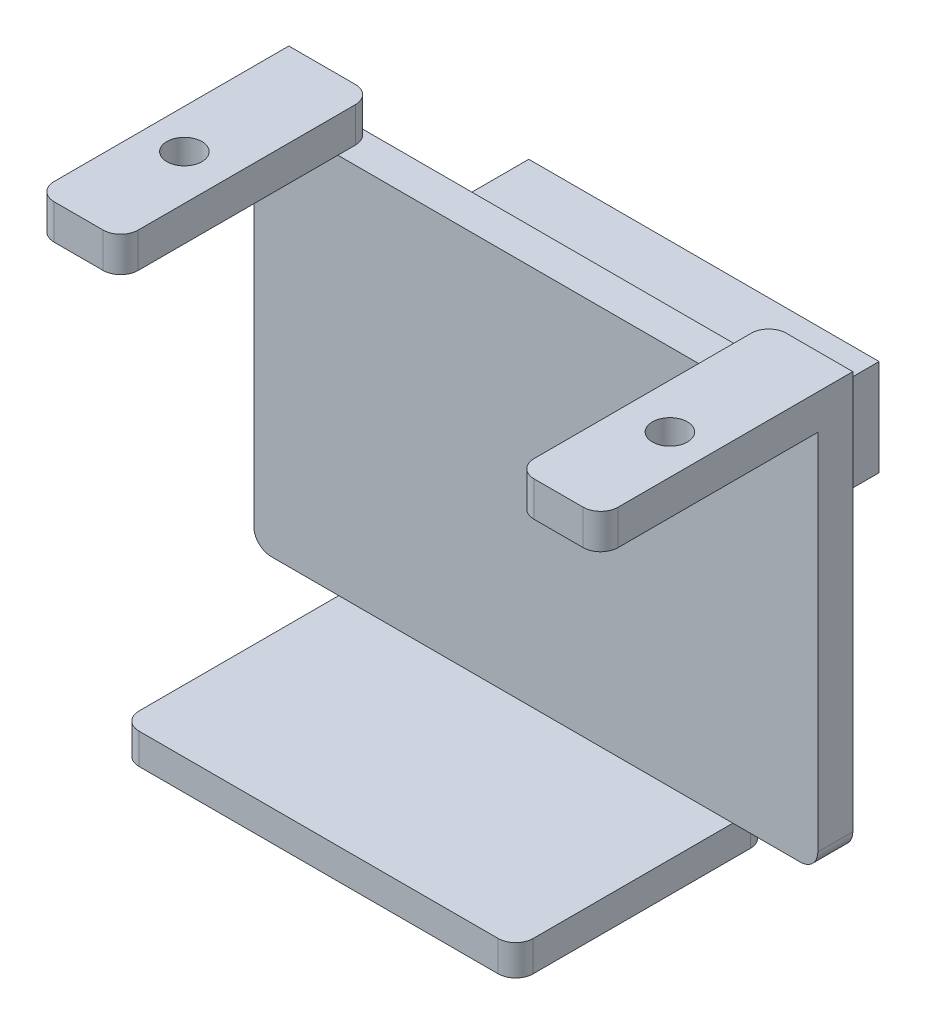
SolidWorks part; units mm, degrees
ref_plane "Front Plane" through (0, 0, 0) normal (0, 0, 1) x (1, 0, 0)
ref_plane "Top Plane" through (0, 0, 0) normal (0, 1, 0) x (1, 0, 0)
ref_plane "Right Plane" through (0, 0, 0) normal (1, 0, 0) x (0, 0, -1)
sketch "Sketch1" plane through (0, 0, 0) normal (0, 0, 1) x (1, 0, 0)
  line L1 (-16.1, 12.75) -> (16.1, 12.75)
  line L2 (-16.1, 12.75) -> (-16.1, -12.75)
  line L3 (-16.1, -12.75) -> (16.1, -12.75)
  line L4 (16.1, 12.75) -> (16.1, -12.75)
  line L5 (-16.1, 12.75) -> (16.1, -12.75) construction
  line L6 (-16.1, -12.75) -> (16.1, 12.75) construction
  point P0 (0, 0)
  dimension "D1" = 32.2
  dimension "D2" = 25.5
extrude "Boss-Extrude1" add sketch "Sketch1" along normal blind 14.4
sketch "Sketch3" plane through (0, 0, 14.4) normal (0, 0, 1) x (1, 0, 0)
  line L0 (-16.1, 12.75) -> (-16.1, -12.75) construction
  line L1 (-16.1, 10.75) -> (16.1, 10.75)
  line L2 (-16.1, 10.75) -> (-16.1, -11)
  line L3 (-16.1, -11) -> (16.1, -11)
  line L4 (16.1, 10.75) -> (16.1, -11)
  line L5 (16.1, -12.75) -> (16.1, 12.75) construction
  line L6 (16.1, 12.75) -> (-16.1, 12.75) construction
  dimension "D1" = 2
  dimension "D2" = 21.75
extrude "Cut-Extrude1" cut sketch "Sketch3" against normal blind 12.4
sketch "Sketch5" plane through (0, 0, 14.4) normal (0, 0, 1) x (1, 0, 0)
  line L0 (16.1, 12.75) -> (-16.1, 12.75) construction
  line L1 (-11.3, 12.75) -> (11.3, 12.75)
  line L2 (-11.3, 12.75) -> (-11.3, 10.75)
  line L3 (-11.3, 10.75) -> (11.3, 10.75)
  line L4 (11.3, 12.75) -> (11.3, 10.75)
  line L5 (16.1, 10.75) -> (-16.1, 10.75) construction
  line L6 (-16.1, 12.75) -> (-16.1, 10.75) construction
  line L7 (16.1, 10.75) -> (16.1, 12.75) construction
  dimension "D1" = 4.8
  dimension "D2" = 4.8
extrude "Cut-Extrude2" cut sketch "Sketch5" against normal blind 14.4 contours L2 L1 L4 L3
fillet "Fillet1" radius 1 1 edges at (-11.3, 11.75, 14.4)
fillet "Fillet2" radius 1 1 edges at (-16.1, 11.75, 14.4)
fillet "Fillet3" radius 1 1 edges at (11.3, 11.75, 14.4)
fillet "Fillet4" radius 1 1 edges at (16.1, 11.75, 14.4)
sketch "Sketch10" plane through (0, 12.75, 0) normal (0, 1, 0) x (1, 0, 0)
  line L0 (-16.1, -13.4) -> (-16.1, 0) construction
  circle A0 centre (-13.86, -8.203) radius 1
  dimension "D1" = 2.24
extrude "Cut-Extrude3" cut sketch "Sketch10" against normal blind 10
mirror "Mirror1" about plane through (0, 0, 0) normal (1, 0, 0) of "Cut-Extrude3"
sketch "Sketch11" plane through (0, 0, 14.4) normal (0, 0, 1) x (1, 0, 0)
  line L0 (-16.1, -12.75) -> (16.1, -12.75) construction
  line L1 (-16.1, -11) -> (-11.25, -11)
  line L2 (-16.1, -11) -> (-16.1, -12.75)
  line L3 (-16.1, -12.75) -> (-11.25, -12.75)
  line L4 (-11.25, -11) -> (-11.25, -12.75)
  dimension "D1" = 4.85
extrude "Cut-Extrude4" cut sketch "Sketch11" against normal blind 20
mirror "Mirror2" about plane through (0, 0, 0) normal (1, 0, 0) of "Cut-Extrude4"
fillet "Fillet5" radius 1 6 edges at (-11.25, -11.875, 0) (-16.1, -11, 1) (16.1, -11, 1) (11.25, -11.875, 0) (11.25, -11.875, 14.4) (-11.25, -11.875, 14.4)
fillet "Fillet6" radius 1 2 edges at (-11.3, 11.75, 0) (11.3, 11.75, 0)
sketch "Sketch12" plane through (0, 0, 0) normal (0, 0, -1) x (-1, 0, 0)
  line L1 (-12.6, 5.5) -> (7.4, 5.5)
  line L2 (-12.6, 5.5) -> (-12.6, 3.5)
  line L3 (-12.6, 3.5) -> (7.4, 3.5)
  line L4 (7.4, 5.5) -> (7.4, 3.5)
  line L6 (12.3, 10.75) -> (-12.3, 10.75) construction
  line L9 (-16.1, -10) -> (-16.1, 12.75) construction
  dimension "D1" = 5.25
  dimension "D2" = 2
  dimension "D3" = 20
  dimension "D4" = 3.5
extrude "Boss-Extrude2" add sketch "Sketch12" along normal blind 5
sketch "Sketch13" plane through (0, 0, 0) normal (0, 0, -1) x (-1, 0, 0)
  line L0 (7.4, 5.5) -> (-12.6, 5.5) construction
  line L1 (-12.6, 9) -> (7.4, 9)
  line L2 (-12.6, 9) -> (-12.6, 7)
  line L3 (-11.6, 7) -> (6.4, 7)
  line L4 (7.4, 9) -> (7.4, 7)
  line L5 (-2.6, 7) -> (-2.6, 5.5) construction
  line L7 (-12.6, 7) -> (-12.6, 5.5)
  line L8 (-12.6, 5.5) -> (-11.6, 5.5)
  line L9 (-11.6, 7) -> (-11.6, 5.5)
  line L10 (7.4, 5.5) -> (-12.6, 5.5) construction
  line L11 (7.4, 5.5) -> (6.4, 5.5)
  line L12 (6.4, 7) -> (6.4, 5.5)
  line L14 (7.4, 7) -> (7.4, 5.5)
  dimension "D1" = 1.5
  dimension "D2" = 1
extrude "Boss-Extrude3" add sketch "Sketch13" along normal blind 5
